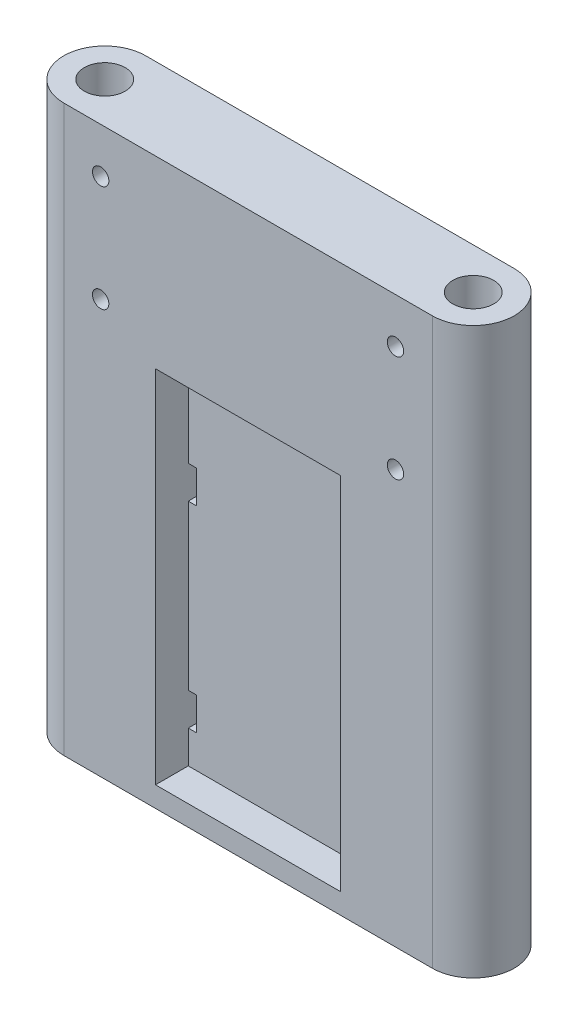
SolidWorks part; units mm, degrees
ref_plane "前视基准面" through (0, 0, 0) normal (0, 0, 1) x (1, 0, 0)
ref_plane "上视基准面" through (0, 0, 0) normal (0, 1, 0) x (1, 0, 0)
ref_plane "右视基准面" through (0, 0, 0) normal (1, 0, 0) x (0, 0, -1)
other "Configuration Table"
sketch "Sketch2" plane through (0, 0, 0) normal (0, 1, 0) x (1, 0, 0)
  line L0 (0, 0) -> (28.575, 0) construction
  line L2 (-28.575, 6.35) -> (28.575, 6.35)
  line L3 (28.575, -6.35) -> (-28.575, -6.35)
  circle A0 centre (28.575, 0) radius 3.175
  arc A1 (28.575, -6.35) -> (28.575, 6.35) centre (28.575, 0) ccw
  circle A2 centre (-28.575, 0) radius 3.175
  arc A3 (-28.575, 6.35) -> (-28.575, -6.35) centre (-28.575, 0) ccw
  dimension "D3" = 6.35
  dimension "D4" = 12.7
  dimension "D5" = 6.35
  dimension "D6" = 12.7
  dimension "D1" = 57.15
  dimension "D2" = 57.15
  dimension "D7" = 12.7
  dimension "D8" = 28.575
extrude "Boss-Extrude1" add sketch "Sketch2" along normal mid plane 87.63
sketch "Sketch5" plane through (0, 0, -6.35) normal (0, 0, -1) x (-1, 0, 0)
  line L0 (0, 36.83) -> (0, 0) construction
  line L4 (0, 55) -> (0, -55) construction
  line L5 (0, 36.83) -> (22.86, 36.83) construction
  line L6 (0, 36.83) -> (-22.86, 36.83) construction
  line L7 (22.86, 36.83) -> (22.86, 20.32) construction
  line L8 (-22.86, 36.83) -> (-22.86, 20.32) construction
  line L9 (0, 36.83) -> (0, 0) construction
  circle A0 centre (22.86, 36.83) radius 1.27
  circle A1 centre (22.86, 20.32) radius 1.27
  circle A2 centre (-22.86, 36.83) radius 1.27
  circle A3 centre (-22.86, 20.32) radius 1.27
  dimension "D4" = 16.51
  dimension "D5" = 16.51
  dimension "D6" = 2.54
  dimension "D7" = 2.54
  dimension "D8" = 2.54
  dimension "D9" = 2.54
  dimension "D1" = 22.86
  dimension "D2" = 36.83
  dimension "D3" = 22.86
extrude "Cut-Extrude1" cut sketch "Sketch5" against normal blind 5.08
sketch "Sketch6" plane through (0, 0, 6.35) normal (0, 0, 1) x (1, 0, 0)
  line L0 (0, 0) -> (0, 36.83) construction
  line L1 (0, -55) -> (0, 55) construction
  line L2 (0, 36.83) -> (22.86, 36.83) construction
  line L3 (0, 36.83) -> (-22.86, 36.83) construction
  line L4 (22.86, 36.83) -> (22.86, 20.32) construction
  line L5 (-22.86, 36.83) -> (-22.86, 20.32) construction
  circle A0 centre (22.86, 36.83) radius 1.27
  circle A1 centre (22.86, 20.32) radius 1.27
  circle A2 centre (-22.86, 36.83) radius 1.27
  circle A3 centre (-22.86, 20.32) radius 1.27
  dimension "D4" = 2.54
  dimension "D6" = 2.54
  dimension "D7" = 2.54
  dimension "D9" = 2.54
  dimension "D1" = 22.86
  dimension "D2" = 36.83
  dimension "D3" = 22.86
  dimension "D5" = 16.51
  dimension "D8" = 16.51
extrude "Cut-Extrude2" cut sketch "Sketch6" against normal through all
sketch "Sketch7" plane through (0, 0, 6.35) normal (0, 0, 1) x (1, 0, 0)
  line L0 (0, 0) -> (0, 15.24) construction
  line L1 (0, -6.985) -> (0, 6.985) construction
  line L2 (0, 15.24) -> (14.351, 15.24) construction
  line L3 (0, 15.24) -> (-14.351, 15.24) construction
  line L5 (-14.351, 15.24) -> (14.351, 15.24)
  line L6 (-14.351, 15.24) -> (-14.351, -40.64)
  line L7 (-14.351, -40.64) -> (14.351, -40.64)
  line L8 (14.351, 15.24) -> (14.351, -40.64)
  dimension "D1" = 15.24
  dimension "D2" = 14.351
  dimension "D3" = 14.351
  dimension "D4" = 55.88
extrude "Cut-Extrude3" cut sketch "Sketch7" against normal blind 5.08
mirror "Mirror1" about plane through (0, 0, 0) normal (0, 0, 1) of "Cut-Extrude3"
sketch "Sketch8" plane through (0, 0, 1.27) normal (0, 0, 1) x (1, 0, 0)
  line L0 (0, 0) -> (0, -35.56) construction
  line L1 (0, -6.985) -> (0, 6.985) construction
  line L2 (0, -35.56) -> (13.081, -35.56) construction
  line L3 (0, -35.56) -> (-13.081, -35.56) construction
  line L4 (13.081, -30.48) -> (13.081, -5.08) construction
  line L5 (13.081, -35.56) -> (14.351, -35.56)
  line L6 (13.081, -35.56) -> (13.081, -30.48)
  line L7 (13.081, -30.48) -> (14.351, -30.48)
  line L8 (14.351, -35.56) -> (14.351, -30.48)
  line L10 (13.081, -5.08) -> (14.351, -5.08)
  line L11 (13.081, -5.08) -> (13.081, 0)
  line L12 (13.081, 0) -> (14.351, 0)
  line L13 (14.351, -5.08) -> (14.351, 0)
  dimension "D1" = 35.56
  dimension "D2" = 13.081
  dimension "D3" = 13.081
  dimension "D4" = 5.08
  dimension "D5" = 1.27
  dimension "D6" = 25.4
  dimension "D7" = 5.08
  dimension "D8" = 1.27
extrude "Cut-Extrude4" cut sketch "Sketch8" against normal through all
mirror "Mirror2" about plane through (0, 0, 0) normal (1, 0, 0) of "Cut-Extrude4"
